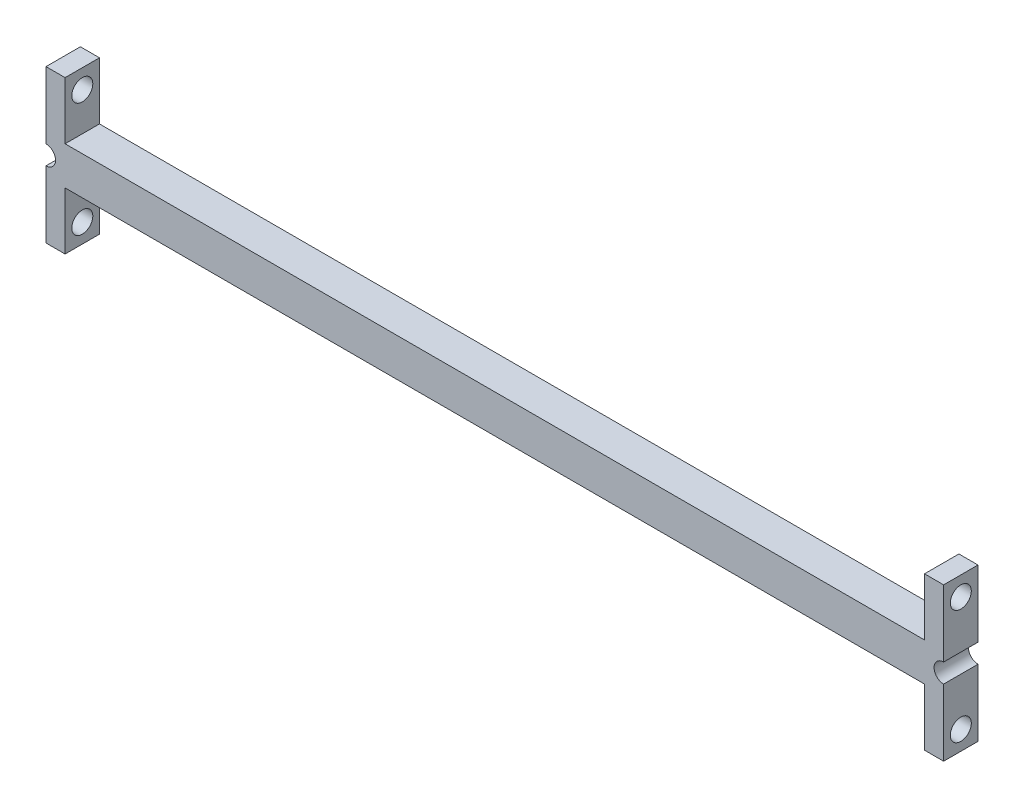
SolidWorks part; units mm, degrees
material "6061 合金"
ref_plane "前视基准面" through (0, 0, 0) normal (0, 0, 1) x (1, 0, 0)
ref_plane "上视基准面" through (0, 0, 0) normal (0, 1, 0) x (1, 0, 0)
ref_plane "右视基准面" through (0, 0, 0) normal (1, 0, 0) x (0, 0, -1)
other "Configuration Table"
sketch "草图1" plane through (0, 0, 0) normal (0, 0, 1) x (1, 0, 0)
  line L1 (0, 0) -> (235, 0)
  line L2 (0, 0) -> (0, -10)
  line L3 (0, -10) -> (235, -10)
  line L4 (235, 0) -> (235, -10)
  dimension "D1" = 235
  dimension "D2" = 10
extrude "凸台-拉伸1" add sketch "草图1" along normal blind 9
sketch "草图2" plane through (0, 0, 9) normal (0, 0, 1) x (1, 0, 0)
  line L1 (230, 15) -> (235, 15)
  line L2 (230, 15) -> (230, -25)
  line L3 (230, -25) -> (235, -25)
  line L4 (235, 15) -> (235, -25)
  line L5 (0, 15) -> (5, 15)
  line L6 (0, 15) -> (0, -25)
  line L7 (0, -25) -> (5, -25)
  line L8 (5, 15) -> (5, -25)
  line L9 (235, -10) -> (235, 0) construction
  line L10 (0, 0) -> (0, -10) construction
  line L11 (235, 0) -> (0, 0) construction
  line L12 (0, -10) -> (235, -10) construction
  dimension "D1" = 15
  dimension "D2" = 15
  dimension "D3" = 5
  dimension "D4" = 15
  dimension "D5" = 15
  dimension "D6" = 5
extrude "凸台-拉伸2" add sketch "草图2" against normal blind 9
sketch "草图3" plane through (0, 0, 9) normal (0, 0, 1) x (1, 0, 0)
  line L0 (235, -25) -> (235, 15) construction
  line L1 (0, 15) -> (0, -25) construction
  circle A0 centre (235, -5) radius 2.5
  circle A1 centre (0, -5) radius 2.5
  dimension "D1" = 5
  dimension "D2" = 5
extrude "切除-拉伸1" cut sketch "草图3" against normal blind 32
sketch "草图4" plane through (0, 0, 0) normal (-1, 0, 0) x (0, 0, 1)
  line L0 (4.5, 12.3561) -> (4.5, -22.0434) construction
  line L1 (9, -7.5) -> (9, -25) construction
  line L2 (0, -7.5) -> (0, -25) construction
  line L3 (-7.6668, -5) -> (20.6936, -5) construction
  line L4 (0, -25) -> (9, -25) construction
  line L5 (0, 15) -> (9, 15) construction
  circle A0 centre (4.5, 10) radius 2.75
  circle A1 centre (4.5, -20) radius 2.75
  dimension "D1" = 5.5
  dimension "D2" = 5
extrude "切除-拉伸2" cut sketch "草图4" against normal through all contours A0 | A1
